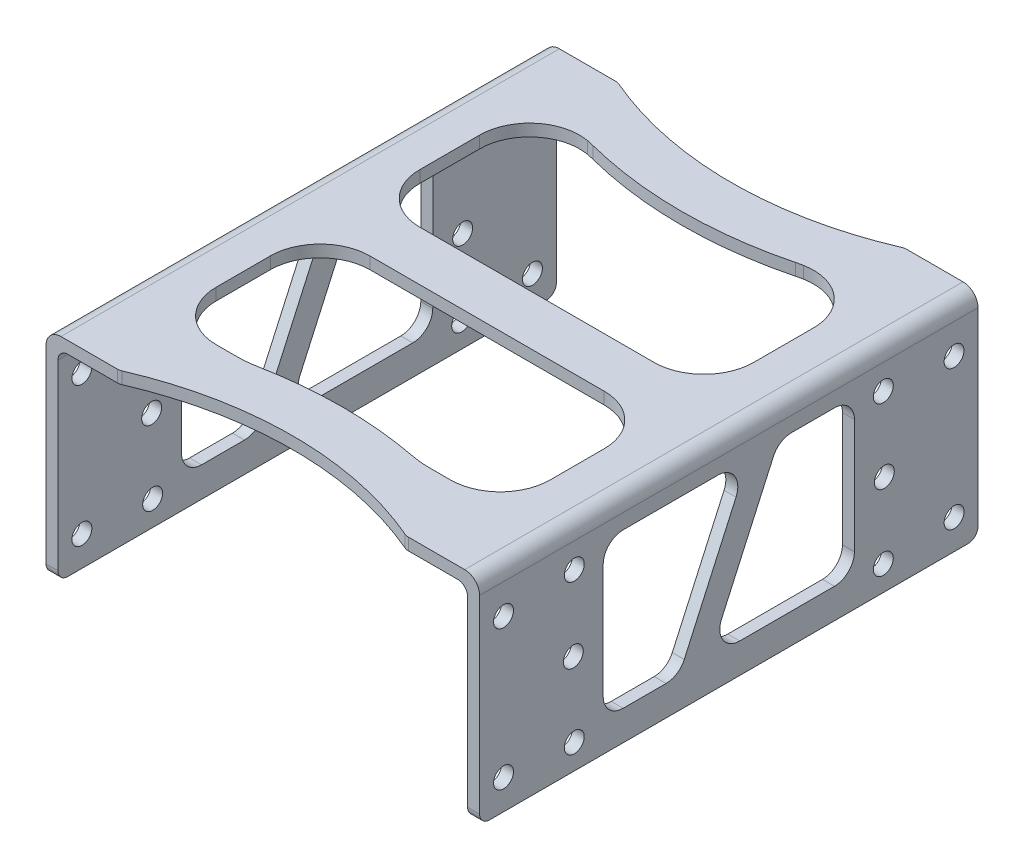
SolidWorks part; units mm, degrees
ref_plane "前视基准面" through (0, 0, 0) normal (0, 0, 1) x (1, 0, 0)
ref_plane "上视基准面" through (0, 0, 0) normal (0, 1, 0) x (1, 0, 0)
ref_plane "右视基准面" through (0, 0, 0) normal (1, 0, 0) x (0, 0, -1)
ref_plane "基准面1" through (0, -20, 0) normal (0, -1, 0) x (1, 0, 0)
sketch "草图1" plane through (0, -20, 0) normal (0, -1, 0) x (1, 0, 0)
  line L0 (21.75, 19) -> (-21.75, 19)
  line L1 (-21.75, 19) -> (-21.75, -31)
  line L2 (-21.75, -31) -> (21.75, -31)
  line L3 (21.75, -31) -> (21.75, 19)
  dimension "D1" = 43.5
  dimension "D2" = 50
extrude "凸台-拉伸1" add sketch "草图1" against normal blind 21.5
sketch "草图2" plane through (0, 0, 19) normal (0, 0, 1) x (1, 0, 0)
  line L0 (-20.55, -22.3682) -> (20.55, -22.3682)
  line L1 (20.55, -22.3682) -> (20.55, 0.3)
  line L2 (20.55, 0.3) -> (-20.55, 0.3)
  line L3 (-20.55, 0.3) -> (-20.55, -22.3682)
  line L4 (0, 1.5) -> (0, -22.3682) construction
  line L5 (21.75, 1.5) -> (-21.75, 1.5) construction
  dimension "D1" = 41.1
  dimension "D2" = 1.2
extrude "切除-拉伸1" cut sketch "草图2" against normal through all
sketch "草图3" plane through (0, 1.5, 0) normal (0, 1, 0) x (-1, 0, 0)
  line L0 (14.3875, 19) -> (-14.3875, 19)
  arc A0 (-14.3875, 19) -> (14.3875, 19) centre (0, 52) ccw
extrude "切除-拉伸2" cut sketch "草图3" against normal through all
sketch "草图4" plane through (0, 1.5, 0) normal (0, 1, 0) x (-1, 0, 0)
  line L0 (-14.3875, -31) -> (14.3875, -31)
  line L1 (21.75, -31) -> (-21.75, -31) construction
  arc A0 (14.3875, -31) -> (-14.3875, -31) centre (0, -64) ccw
  dimension "D1" = 28.775
extrude "切除-拉伸3" cut sketch "草图4" against normal through all
hole_wizard "Ø2.0 (2) 直径孔1" positions "草图8" profile "草图7" hole size "Ø2.0" standard "ANSI Metric"
sketch "草图8" plane through (20.55, 0, 0) normal (-1, 0, 0) x (0, 0, 1)
  line L0 (-21.5, -2.5) -> (-21.5, -17.5) construction
  line L2 (-28.6, -3) -> (-28.6, -17) construction
  line L4 (19, 1.5) -> (19, -20) construction
  line L5 (-31, 1.5) -> (-31, -20) construction
  point P0 (16.6, -3)
  point P1 (16.6, -17)
  point P2 (9.5, -17.5)
  point P3 (9.6, -10)
  point P4 (9.5, -2.5)
  point P5 (-21.5, -2.5)
  point P6 (-28.6, -3)
  point P7 (-28.6, -17)
  point P8 (-21.5, -17.5)
  point P9 (-21.6, -10)
  dimension "D1" = 14
  dimension "D2" = 7.5
  dimension "D3" = 7.5
  dimension "D4" = 7.1
  dimension "D5" = 0.1
  dimension "D6" = 2.4
  dimension "D7" = 2.4
sketch "草图7" plane through (20.55, -3, 16.6) normal (0, 1, 0) x (0, 0, 1)
  line L0 (0, 0) -> (0, 1.2)
  line L1 (0, 1.2) -> (1, 1.2)
  line L2 (1, 1.2) -> (1, 0)
  line L5 (1, 0) -> (0, 0)
  line L11 (0, -6.35) -> (0, 107.95) construction
  dimension "通孔孔直径" = 2
  dimension "通孔孔深度" = 1.2
hole_wizard "Ø2.0 (2) 直径孔2" positions "草图12" profile "草图11" hole size "Ø2.0" standard "ANSI Metric"
sketch "草图12" plane through (-20.55, 0, 0) normal (1, 0, 0) x (0, 0, -1)
  line L0 (21.5, -2.5) -> (21.5, -17.5) construction
  line L2 (28.6, -3) -> (28.6, -17) construction
  line L4 (31, 1.5) -> (31, -20) construction
  point P0 (-16.6, -3)
  point P1 (-16.6, -17)
  point P2 (-9.5, -17.5)
  point P3 (-9.6, -10)
  point P4 (-9.5, -2.5)
  point P5 (21.5, -2.5)
  point P6 (28.6, -3)
  point P7 (28.6, -17)
  point P8 (21.5, -17.5)
  point P9 (21.6, -10)
  dimension "D1" = 7.1
  dimension "D2" = 0.1
  dimension "D3" = 14
  dimension "D4" = 15
  dimension "D5" = 7.5
  dimension "D6" = 2.4
sketch "草图11" plane through (-20.55, -3, 16.6) normal (0, 1, 0) x (0, 0, -1)
  line L0 (0, 0) -> (0, 1.2)
  line L1 (0, 1.2) -> (1, 1.2)
  line L2 (1, 1.2) -> (1, 0)
  line L5 (1, 0) -> (0, 0)
  line L11 (0, -6.35) -> (0, 107.95) construction
  dimension "通孔孔直径" = 2
  dimension "通孔孔深度" = 1.2
fillet "圆角1" radius 1 8 edges at (14.3875, 0.9, 19) (-14.3875, 0.9, 19) (21.15, -20, 19) (-14.3875, 0.9, -31) (14.3875, 0.9, -31) (-21.15, -20, -31) (21.15, -20, -31) (-21.15, -20, 19)
fillet "圆角2" radius 1.5 2 edges at (21.75, 1.5, -6) (-21.75, 1.5, -6)
sketch "草图13" plane through (21.75, 0, 0) normal (1, 0, 0) x (0, 0, -1)
  line L0 (-19, -9.5) -> (31, -9.5) construction
  line L1 (-19, 0) -> (-19, -19) construction
  line L2 (31, 0) -> (31, -19) construction
  line L3 (6, 0) -> (6, -20) construction
  line L4 (31, 0) -> (-19, 0) construction
  line L5 (30, -20) -> (-18, -20) construction
  circle A0 centre (6, -9.5) radius 4
  dimension "D1" = 8
extrude "切除-拉伸4" [suppressed] cut sketch "草图13" against normal through all
fillet "圆角3" radius 1 2 edges at (20.55, 0.3, -6) (-20.55, 0.3, -6)
sketch "草图14" plane through (0, 1.5, 0) normal (0, 1, 0) x (1, 0, 0)
  line L0 (21.75, 31) -> (21.75, -19) construction
  line L1 (-16.75, 24.5976) -> (16.75, 24.5976)
  line L2 (-16.75, 24.5976) -> (-16.75, -11.9219)
  line L3 (-16.75, -11.9219) -> (16.75, -11.9219)
  line L4 (16.75, 24.5976) -> (16.75, -11.9219)
  line L5 (-21.75, -19) -> (-21.75, 31) construction
  line L6 (-21.75, 6) -> (21.75, 6) construction
  line L7 (-16.75, 8.5) -> (16.75, 8.5)
  line L8 (-16.75, 8.5) -> (-16.75, 3.5)
  line L9 (-16.75, 3.5) -> (16.75, 3.5)
  line L10 (16.75, 8.5) -> (16.75, 3.5)
  circle A0 centre (0, 64) radius 36
  arc A1 (-14.2001, 30.9189) -> (14.2001, 30.9189) centre (0, 64) ccw construction
  circle A2 centre (0, 64) radius 41
  circle A3 centre (0, -52) radius 36
  arc A4 (14.2001, -18.9189) -> (-14.2001, -18.9189) centre (0, -52) ccw construction
  circle A5 centre (0, -52) radius 41
  dimension "D3" = 5
  dimension "D4" = 5
  dimension "D1" = 5
  dimension "D2" = 5
  dimension "D5" = 5
extrude "切除-拉伸5" cut sketch "草图14" against normal blind 10 contours A2 L1 L2 L7 L4 | A5 L3 L4 L9 L2
fillet "圆角4" radius 10 4 edges at (-8.6454, 0.9, 11.9219) (8.6454, 0.9, 11.9219) (11.3335, 0.9, -24.5976) (-11.3335, 0.9, -24.5976)
fillet "圆角5" radius 5 8 edges at (-16.75, 0.9, 11.9219) (-16.75, 0.9, -3.5) (16.75, 0.9, 11.9219) (16.75, 0.9, -3.5) (16.75, 0.9, -8.5) (16.75, 0.9, -24.5976) (-16.75, 0.9, -8.5) (-16.75, 0.9, -24.5976)
sketch "草图15" plane through (-21.75, 0, 0) normal (-1, 0, 0) x (0, 0, 1)
  line L0 (-31, 1.5) -> (19, 1.5) construction
  line L1 (-18.6, -1.5) -> (6.6, -1.5)
  line L2 (-18.6, -1.5) -> (-18.6, -17)
  line L3 (-18.6, -17) -> (6.6, -17)
  line L4 (6.6, -1.5) -> (6.6, -17)
  line L5 (18, -20) -> (-30, -20) construction
  line L6 (-11, -1.5) -> (-4, -17)
  line L7 (-8, -1.5) -> (-1, -17)
  line L8 (-6, -1.5) -> (-6, -17) construction
  circle A0 centre (9.6, -10) radius 1 construction
  circle A1 centre (-21.6, -10) radius 1 construction
  point P18 (-11.1964, -1.5)
  dimension "D4" = 3
  dimension "D1" = 3
  dimension "D2" = 3
  dimension "D3" = 3
  dimension "D5" = 2
  dimension "D6" = 2
  dimension "D7" = 3
extrude "切除-拉伸6" cut sketch "草图15" against normal through all contours L8 L6 L1 L2 L3 | L6 L8 L3 | L1 L8 L7 L3 L4 | L8 L1 L7
fillet "圆角6" radius 2 8 edges at (-21.15, -17, 6.6) (-21.15, -17, -1) (-21.15, -17, -4) (-21.15, -17, -18.6) (-21.15, -1.5, -8) (-21.15, -1.5, 6.6) (-21.15, -1.5, -11) (-21.15, -1.5, -18.6)
fillet "圆角7" radius 2 8 edges at (21.15, -17, -18.6) (21.15, -1.5, -18.6) (21.15, -1.5, -11) (21.15, -17, -4) (21.15, -17, -1) (21.15, -17, 6.6) (21.15, -1.5, 6.6) (21.15, -1.5, -8)
